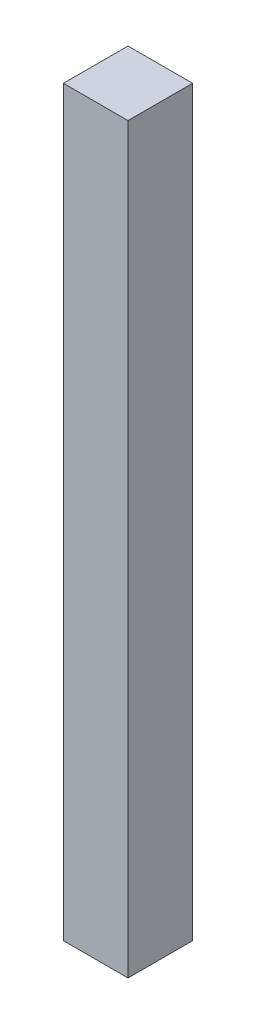
SolidWorks part; units mm, degrees
material "Mahogany"
ref_plane "Front Plane" through (0, 0, 0) normal (0, 0, 1) x (1, 0, 0)
ref_plane "Top Plane" through (0, 0, 0) normal (0, 1, 0) x (1, 0, 0)
ref_plane "Right Plane" through (0, 0, 0) normal (1, 0, 0) x (0, 0, -1)
sketch "Sketch1" plane through (0, 0, 0) normal (1, 0, 0) x (0, 0, -1)
  line L1 (25, -287.5) -> (-25, -287.5)
  line L2 (25, -287.5) -> (25, 287.5)
  line L3 (25, 287.5) -> (-25, 287.5)
  line L4 (-25, -287.5) -> (-25, 287.5)
  line L5 (25, -287.5) -> (-25, 287.5) construction
  line L6 (25, 287.5) -> (-25, -287.5) construction
  point P0 (0, 0)
  dimension "D1" = 575
  dimension "D2" = 50
extrude "Boss-Extrude1" add sketch "Sketch1" along normal blind 50
